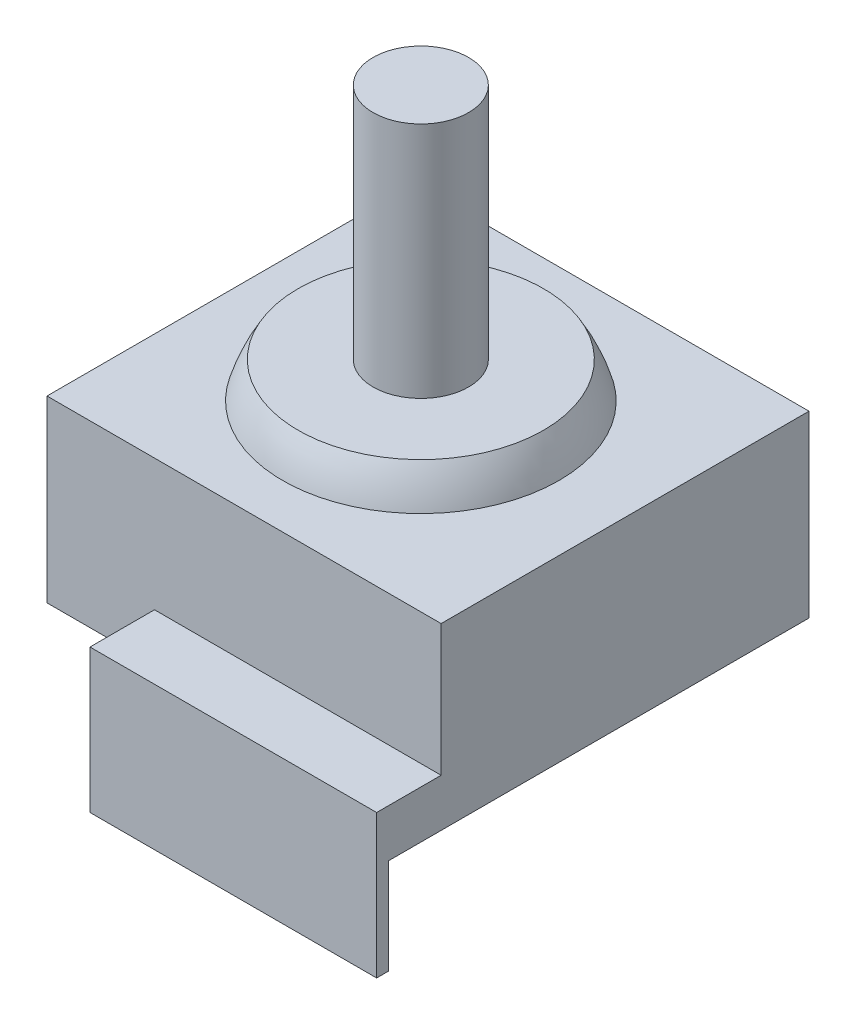
SolidWorks part; units mm, degrees
ref_plane "前视基准面" through (0, 0, 0) normal (0, 0, 1) x (1, 0, 0)
ref_plane "上视基准面" through (0, 0, 0) normal (0, 1, 0) x (1, 0, 0)
ref_plane "右视基准面" through (0, 0, 0) normal (1, 0, 0) x (0, 0, -1)
sketch "草图1" plane through (0, 0, 0) normal (0, 1, 0) x (1, 0, 0)
  line L1 (-8, -7.65) -> (8.5, -7.65)
  line L2 (-8, -7.65) -> (-8, 7.75)
  line L3 (-8, 7.75) -> (8.5, 7.75)
  line L4 (8.5, -7.65) -> (8.5, 7.75)
  circle A0 centre (0, 0) radius 0.5
  dimension "D5" = 1
  dimension "D1" = 16.5
  dimension "D2" = 15.4
  dimension "D3" = 8
  dimension "D4" = 7.65
extrude "凸台-拉伸1" add sketch "草图1" along normal blind 7.5
sketch "草图2" plane through (0, 0, 0) normal (0, -1, 0) x (1, 0, 0)
  line L1 (8.5, 7.65) -> (-3.5, 7.65)
  line L2 (8.5, 7.65) -> (8.5, 10.35)
  line L3 (8.5, 10.35) -> (-3.5, 10.35)
  line L4 (-3.5, 7.65) -> (-3.5, 10.35)
  dimension "D1" = 12
  dimension "D2" = 2.7
extrude "凸台-拉伸2" add sketch "草图2" against normal blind 2
sketch "草图3" plane through (0, 2, 0) normal (0, 1, 0) x (1, 0, 0)
  line L0 (8.5, -7.65) -> (8.5, -10.35) construction
  line L1 (-3.5, -10.35) -> (8.5, -10.35)
  line L2 (-3.5, -10.35) -> (-3.5, -9.85)
  line L3 (-3.5, -9.85) -> (8.5, -9.85)
  line L4 (8.5, -10.35) -> (8.5, -9.85)
  dimension "D1" = 0.5
extrude "凸台-拉伸3" add sketch "草图3" against normal blind 6
sketch "草图4" plane through (0, 7.5, 0) normal (0, 1, 0) x (1, 0, 0)
  circle A0 centre (0, 0) radius 0.5 construction
  circle A1 centre (0, 0) radius 0.5 construction
  circle A2 centre (0, 0) radius 2
  dimension "D1" = 4
extrude "凸台-拉伸4" add sketch "草图4" along normal blind 11.45
sketch "草图5" plane through (0, 0, 0) normal (0, 0, 1) x (1, 0, 0)
  line L0 (0, 0) -> (0, 12.5288) construction
  line L1 (0, 9) -> (5.1371, 9)
  line L2 (0, 5.9) -> (6, 5.9)
  line L3 (-8, 0) -> (-3.5, 0) construction
  line L4 (0, 9) -> (0, 5.9)
  arc A0 (5.1371, 9) -> (6, 5.9) centre (0, 5.9) cw
  dimension "D3" = 6
  dimension "D1" = 5.9
  dimension "D2" = 9
revolve "旋转1" add sketch "草图5" angle 360 about L0
